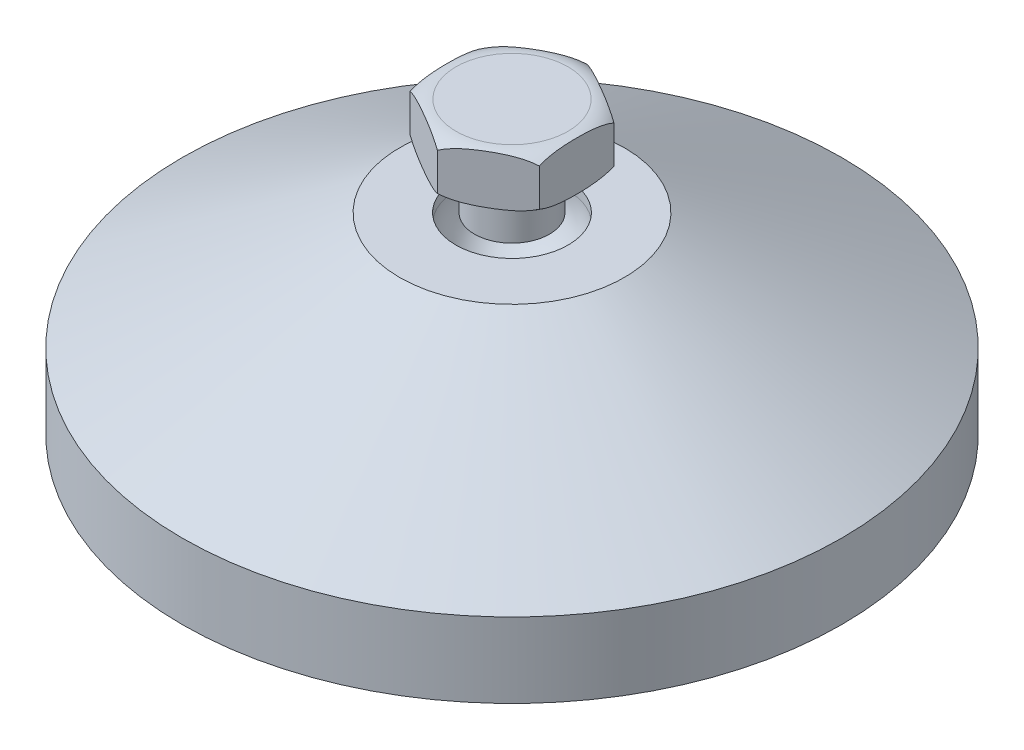
SolidWorks part; units mm, degrees
ref_plane "Front Plane" through (0, 0, 0) normal (0, 0, 1) x (1, 0, 0)
ref_plane "Top Plane" through (0, 0, 0) normal (0, 1, 0) x (1, 0, 0)
ref_plane "Right Plane" through (0, 0, 0) normal (1, 0, 0) x (0, 0, -1)
sketch "Sketch1" plane through (0, 0, 0) normal (0, 0, 1) x (1, 0, 0)
  line L0 (0, 280.7082) -> (0, 0) construction
  line L2 (35.2, 0) -> (35.2, 8)
  line L3 (35.2, 8) -> (12, 20.5)
  line L9 (12, 20.5) -> (6, 20.5)
  line L10 (6, 20.5) -> (6, 19.5)
  line L18 (3.75, 0) -> (3.75, 2.5)
  line L19 (3.75, 0) -> (35.2, 0)
  line L31 (3.75, 2.5) -> (0, 2.5)
  line L32 (0, 2.5) -> (0, 14.0228)
  arc A4 (0, 14.0228) -> (6, 19.5) centre (0.5, 19.5) ccw
  dimension "D14" = 5.5
  dimension "D1" = 35.2
  dimension "D2" = 8
  dimension "D3" = 24
  dimension "D4" = 20.5
  dimension "D12" = 12
  dimension "D13" = 1
  dimension "D15" = 7.5
  dimension "D16" = 2.5
revolve "Revolve1" add sketch "Sketch1" angle 360 about L0
sketch "Sketch7" plane through (0, 0, 0) normal (0, 0, 1) x (1, 0, 0)
  line L0 (4, 20.5) -> (4, 25.5)
  line L1 (4, 25.5) -> (0, 25.5)
  line L3 (0, 20.5) -> (4, 20.5)
  line L4 (0, 25.5) -> (0, 20.5)
  line L5 (12, 20.5) -> (-12, 20.5) construction
  line L6 (6, 20.5) -> (-6, 20.5) construction
  dimension "D1" = 5
  dimension "D2" = 4
revolve "Revolve2" add sketch "Sketch7" angle 360 about L4
sketch "Sketch8" plane through (0, 25.5, 0) normal (0, 1, 0) x (1, 0, 0)
  line L1 (0, 7.9674) -> (-6.9, 3.9837)
  line L2 (-6.9, 3.9837) -> (-6.9, -3.9837)
  line L3 (-6.9, -3.9837) -> (0, -7.9674)
  line L4 (0, -7.9674) -> (6.9, -3.9837)
  line L5 (6.9, -3.9837) -> (6.9, 3.9837)
  line L6 (6.9, 3.9837) -> (0, 7.9674)
  circle A0 centre (0, 0) radius 6.9 construction
  dimension "D1" = 13.8
extrude "Extrude3" add sketch "Sketch8" along normal blind 5.5
sketch "Sketch10" plane through (0, 0, 0) normal (1, 0, 0) x (0, 0, -1)
  line L0 (-7.9674, 31) -> (-7.9674, 30.25)
  line L1 (-7.9674, 31) -> (-7.9674, 25.5) construction
  line L2 (-7.9674, 31) -> (-5.9756, 31)
  line L3 (-7.9674, 31) -> (-3.9837, 31) construction
  line L4 (-7.9674, 28.25) -> (7.9674, 28.25) construction
  line L5 (7.9674, 31) -> (7.9674, 25.5) construction
  line L6 (-7.9674, 25.5) -> (-5.9756, 25.5)
  line L7 (-7.9674, 25.5) -> (-7.9674, 26.25)
  line L8 (0, 31) -> (0, 41.4972) construction
  line L9 (-3.9837, 31) -> (3.9837, 31) construction
  arc A0 (-5.9756, 31) -> (-7.9674, 30.25) centre (-5.9756, 27.98) ccw
  arc A1 (-5.9756, 25.5) -> (-7.9674, 26.25) centre (-5.9756, 28.52) cw
  dimension "D1" = 4
revolve "Cut-Revolve1" cut sketch "Sketch10" angle 360 about L8
